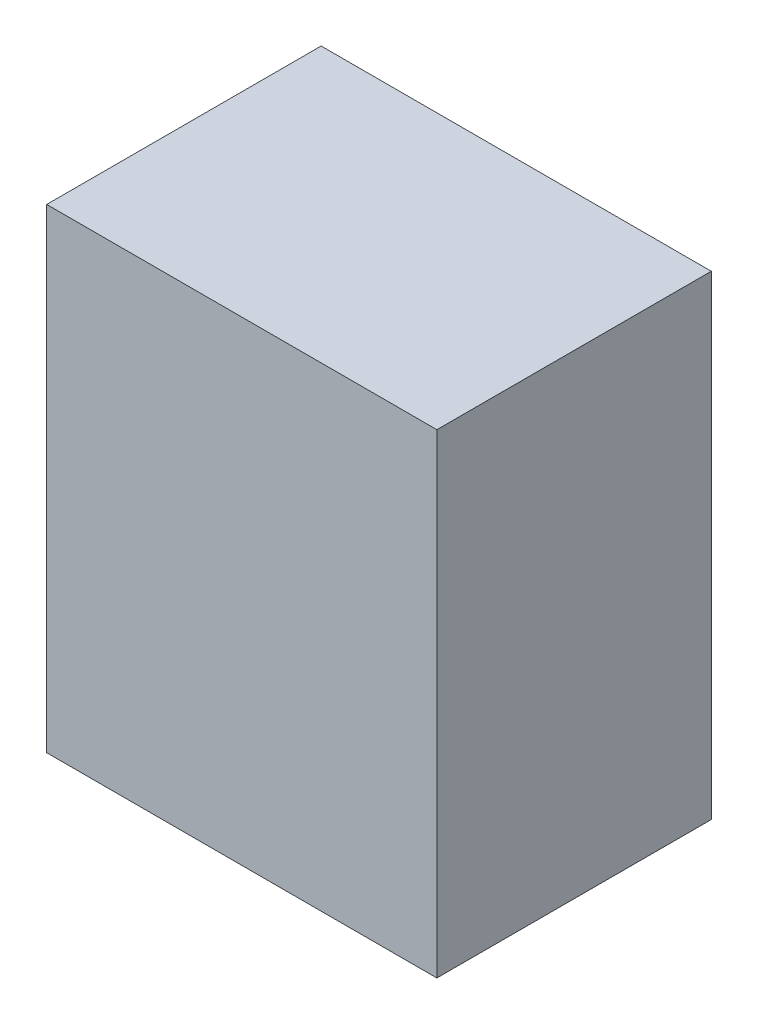
SolidWorks part; units mm, degrees
ref_plane "Alzado" through (0, 0, 0) normal (0, 0, 1) x (1, 0, 0)
ref_plane "Planta" through (0, 0, 0) normal (0, 1, 0) x (1, 0, 0)
ref_plane "Vista lateral" through (0, 0, 0) normal (1, 0, 0) x (0, 0, -1)
sketch "Croquis1" plane through (0, 0, 0) normal (0, 1, 0) x (1, 0, 0)
  line L1 (-155.2103, 95.9007) -> (34.5805, 95.9007)
  line L2 (-155.2103, 95.9007) -> (-155.2103, -37.5963)
  line L3 (-155.2103, -37.5963) -> (34.5805, -37.5963)
  line L4 (34.5805, 95.9007) -> (34.5805, -37.5963)
  line L5 (-155.2103, 95.9007) -> (34.5805, -37.5963) construction
  line L6 (-155.2103, -37.5963) -> (34.5805, 95.9007) construction
  point P0 (-60.3149, 29.1522)
extrude "Saliente-Extruir1" add sketch "Croquis1" along normal blind 231
